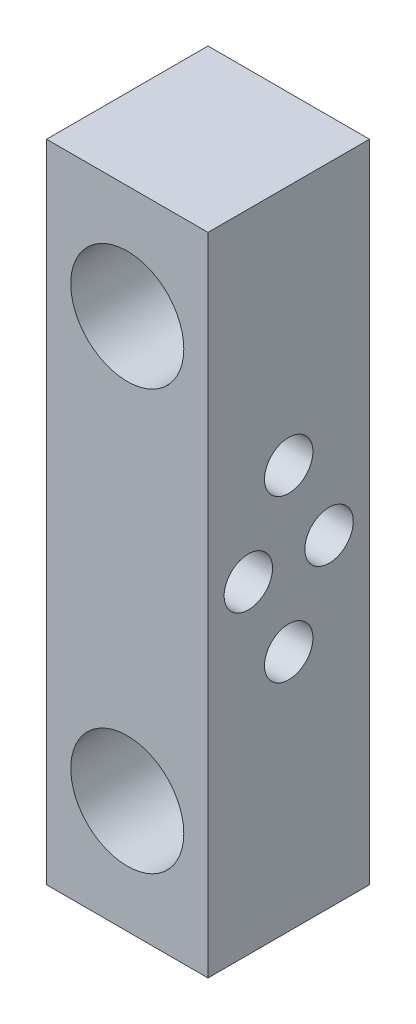
SolidWorks part; units mm, degrees
ref_plane "前视基准面" through (0, 0, 0) normal (0, 0, 1) x (1, 0, 0)
ref_plane "上视基准面" through (0, 0, 0) normal (0, 1, 0) x (1, 0, 0)
ref_plane "右视基准面" through (0, 0, 0) normal (1, 0, 0) x (0, 0, -1)
sketch "草图1" plane through (0, 0, 0) normal (0, 0, 1) x (1, 0, 0)
  line L0 (0, -0.1405) -> (0, -9.9531) construction
  line L1 (-5, 20) -> (5, 20)
  line L2 (-5, 20) -> (-5, -20)
  line L3 (-5, -20) -> (5, -20)
  line L4 (5, 20) -> (5, -20)
  line L5 (-5, 20) -> (5, -20) construction
  line L6 (-5, -20) -> (5, 20) construction
  circle A0 centre (0, 13) radius 3.5
  circle A1 centre (0, -13) radius 3.5
  point P0 (0, 0)
  point P20 (0, 0)
  point P21 (0, 0)
  point P22 (0, 0)
  point P23 (0, 0)
  dimension "D2" = 7
  dimension "D1" = 10
  dimension "D3" = 13
  dimension "D4" = 13
  dimension "D5" = 40
extrude "凸台-拉伸1" add sketch "草图1" along normal blind 10
sketch "草图2" plane through (5, 0, 0) normal (1, 0, 0) x (0, 0, -1)
  line L0 (-10, 20) -> (0, 20) construction
  line L1 (-5, 20.2227) -> (-5, 13.6934) construction
  line L3 (0, 0) -> (-13.3392, 0) construction
  circle A0 centre (-5, 5) radius 1.5
  circle A1 centre (-5, -5) radius 1.5
  circle A3 centre (-2.5, 0) radius 1.5
  circle A4 centre (-7.5, 0) radius 1.5
  point P3 (-5, 20)
  dimension "D2" = 3
  dimension "D3" = 3
  dimension "D5" = 2.5
  dimension "D7" = 3
  dimension "D1" = 5
  dimension "D4" = 5
  dimension "D6" = 2.5
extrude "切除-拉伸1" cut sketch "草图2" against normal through all
